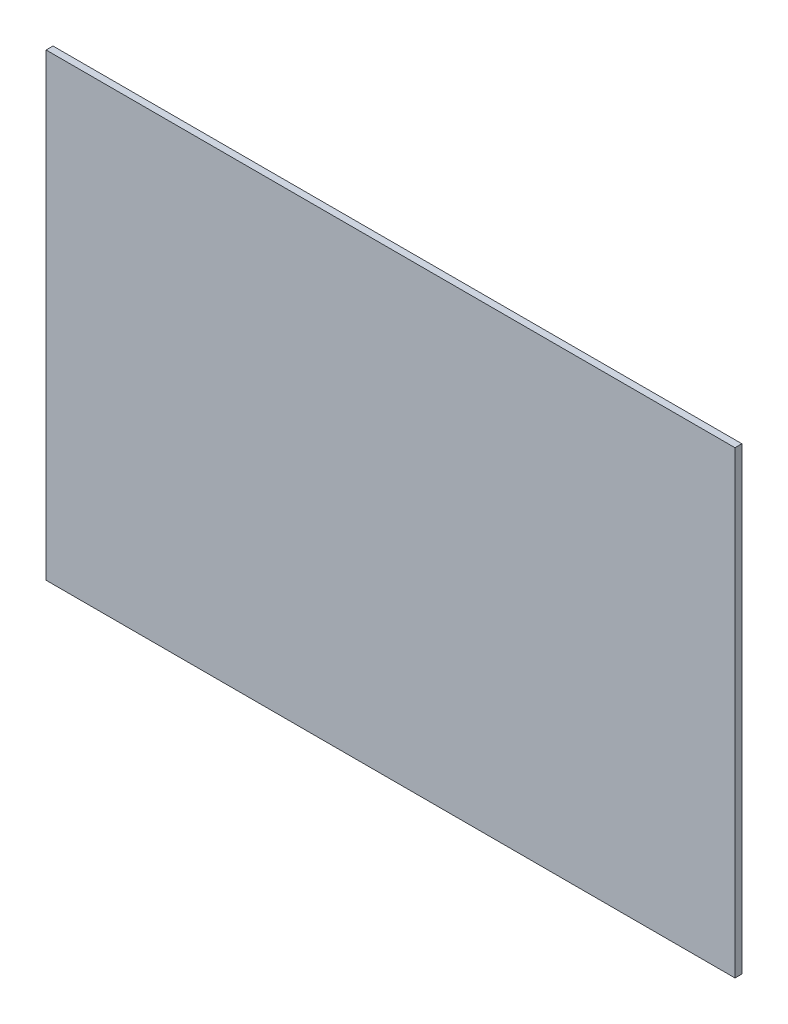
SolidWorks part; units mm, degrees
ref_plane "Plano frontal" through (0, 0, 0) normal (0, 0, 1) x (1, 0, 0)
ref_plane "Plano superior" through (0, 0, 0) normal (0, 1, 0) x (1, 0, 0)
ref_plane "Plano direito" through (0, 0, 0) normal (1, 0, 0) x (0, 0, -1)
sketch "Esboço1" plane through (0, 0, 0) normal (0, 0, 1) x (1, 0, 0)
  line L1 (0, 0) -> (600, 0)
  line L2 (0, 0) -> (0, 400)
  line L3 (0, 400) -> (600, 400)
  line L4 (600, 0) -> (600, 400)
  dimension "D1" = 600
  dimension "D2" = 400
extrude "Ressalto-extrusão1" add sketch "Esboço1" along normal blind 6
